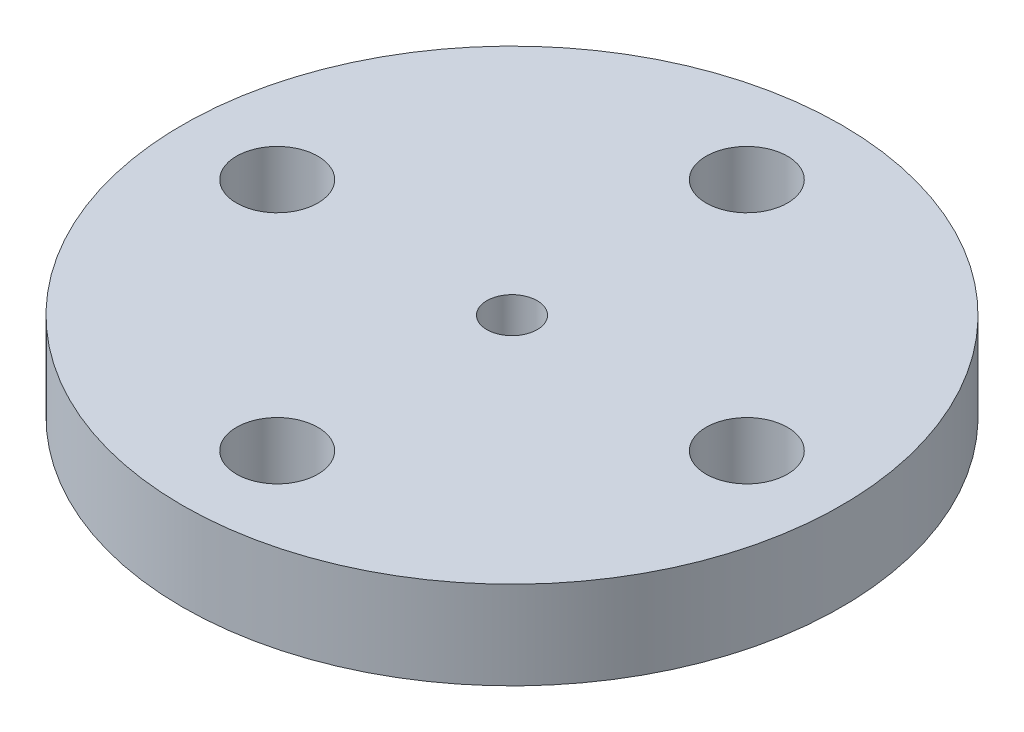
SolidWorks part; units mm, degrees
ref_plane "Front Plane" through (0, 0, 0) normal (0, 0, 1) x (1, 0, 0)
ref_plane "Top Plane" through (0, 0, 0) normal (0, 1, 0) x (1, 0, 0)
ref_plane "Right Plane" through (0, 0, 0) normal (1, 0, 0) x (0, 0, -1)
sketch "Sketch6" plane through (0, 0, 0) normal (0, 1, 0) x (1, 0, 0)
  circle A0 centre (0, 0) radius 9.9822
  circle A1 centre (-7.112, 0) radius 1.2319
  circle A2 centre (0, 7.112) radius 1.2319
  circle A3 centre (7.112, 0) radius 1.2319
  circle A4 centre (0, -7.112) radius 1.2319
  circle A5 centre (0, 0) radius 0.762
  dimension "D1" = 19.9644
  dimension "D2" = 2.4638
  dimension "D3" = 2.4638
  dimension "D4" = 2.4638
  dimension "D5" = 2.4638
  dimension "D10" = 1.524
  dimension "D6" = 7.112
  dimension "D7" = 7.112
  dimension "D8" = 7.112
  dimension "D9" = 7.112
extrude "Boss-Extrude4" add sketch "Sketch6" along normal blind 2.667
